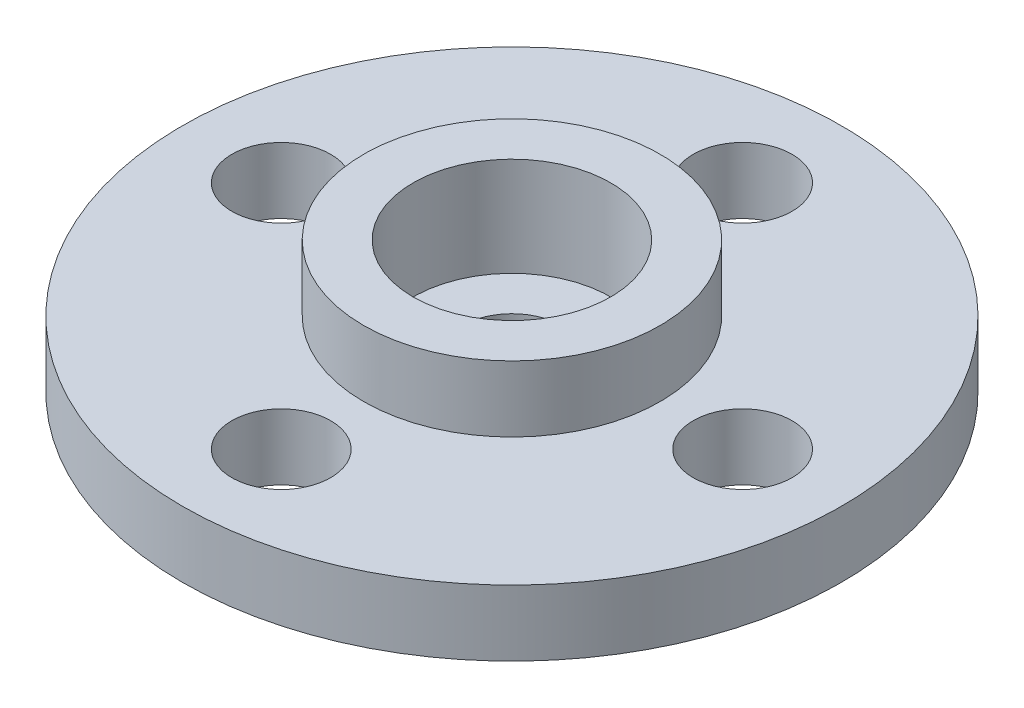
SolidWorks part; units mm, degrees
ref_plane "Спереди" through (0, 0, 0) normal (0, 0, 1) x (1, 0, 0)
ref_plane "Сверху" through (0, 0, 0) normal (0, 1, 0) x (1, 0, 0)
ref_plane "Справа" through (0, 0, 0) normal (1, 0, 0) x (0, 0, -1)
sketch "Эскиз1" plane through (0, 0, 0) normal (0, 1, 0) x (1, 0, 0)
  circle A0 centre (0, 0) radius 10
  dimension "D1" = 20
extrude "тело" add sketch "Эскиз1" along normal blind 2
sketch "Эскиз2" plane through (0, 2, 0) normal (0, 1, 0) x (1, 0, 0)
  circle A0 centre (0, 0) radius 4.5
  dimension "D1" = 9
extrude "выступ крепления к оси" add sketch "Эскиз2" along normal blind 2
sketch "Эскиз3" plane through (0, 4, 0) normal (0, 1, 0) x (1, 0, 0)
  circle A0 centre (0, 0) radius 3
  dimension "D1" = 6
extrude "ось сервы" cut sketch "Эскиз3" against normal blind 3
sketch "Эскиз4" plane through (0, 1, 0) normal (0, 1, 0) x (1, 0, 0)
  circle A0 centre (0, 0) radius 1.5
  dimension "D1" = 3
extrude "отверстие в оси" cut sketch "Эскиз4" against normal through all
sketch "Эскиз5" plane through (0, 2, 0) normal (0, 1, 0) x (1, 0, 0)
  circle A0 centre (0, 0) radius 7 construction
  circle A1 centre (7, 0) radius 1.5
  dimension "D1" = 14
  dimension "D2" = 3
extrude "крепление к детали" cut sketch "Эскиз5" against normal through all
pattern_circular "Круговой массив1" count 4 every 90 about axis through (0, 0, 0) along (0, 1, 0) of "крепление к детали"
